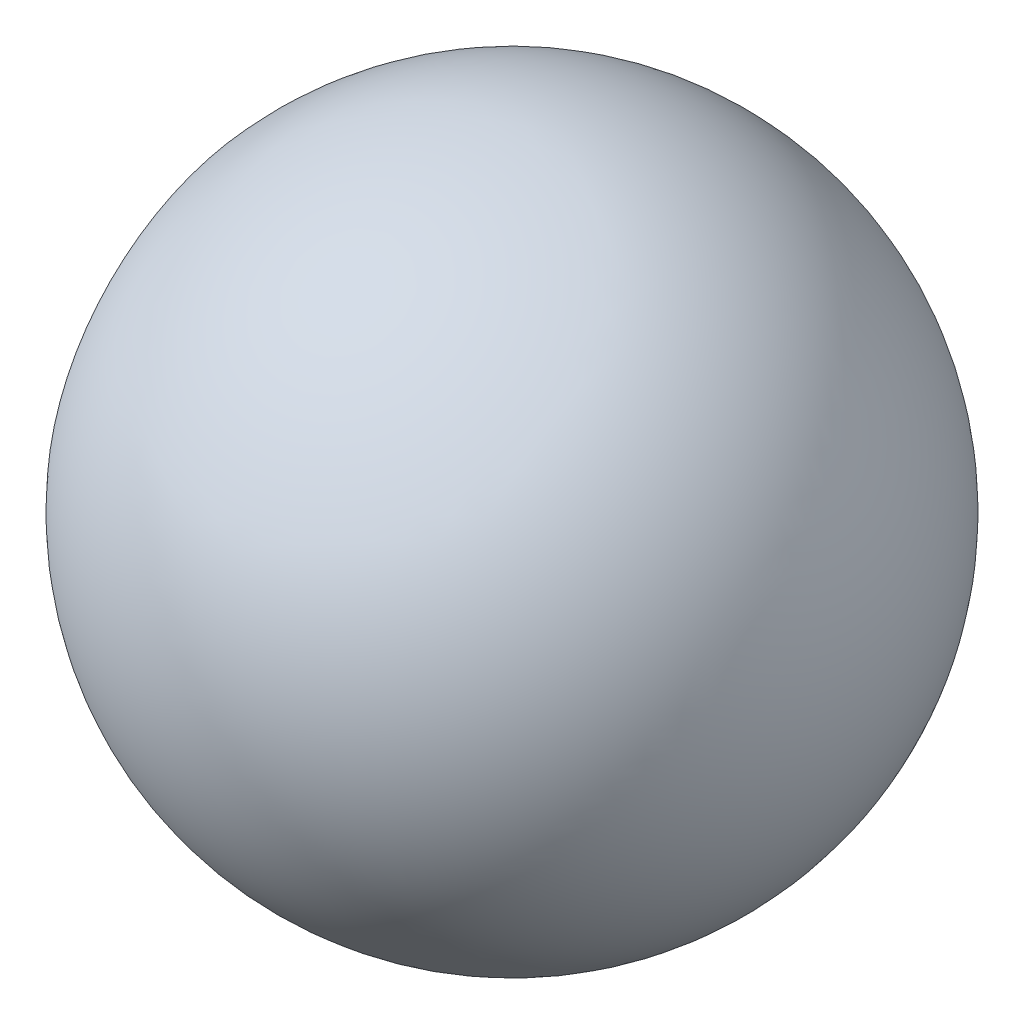
SolidWorks part; units mm, degrees
ref_plane "Front Plane" through (0, 0, 0) normal (0, 0, 1) x (1, 0, 0)
ref_plane "Top Plane" through (0, 0, 0) normal (0, 1, 0) x (1, 0, 0)
ref_plane "Right Plane" through (0, 0, 0) normal (1, 0, 0) x (0, 0, -1)
sketch "Sketch1" plane through (0, 0, 0) normal (0, 0, 1) x (1, 0, 0)
  line L0 (8, 0) -> (-6, 0)
  line L1 (-6, 5.2915) -> (-6, 0)
  arc A0 (8, 0) -> (-6, 5.2915) centre (0, 0) ccw
  dimension "D1" = 8
  dimension "D2" = 6
revolve "Revolve1" add sketch "Sketch1" angle 360 about L0
hole_wizard "M6 Tapped Hole1" positions "Sketch2" profile "Sketch3" tap size "M6" standard "ISO"
sketch "Sketch2" plane through (-6, 0, 0) normal (-1, 0, 0) x (0, 0, 1)
  point P0 (0, 0)
sketch "Sketch3" plane through (-6, 0, 0) normal (0, 1, 0) x (0, 0, 1)
  line L0 (0, 0) -> (0, 11.5022)
  line L1 (0, 11.5022) -> (2.5, 10)
  line L2 (2.5, 10) -> (2.5, 0)
  line L5 (2.5, 0) -> (0, 0)
  line L10 (0, 11.5022) -> (-2.5, 10) construction
  line L11 (0, -6.35) -> (0, 107.95) construction
  dimension "Tap Drill Dia." = 5
  dimension "Tap Drill Depth" = 10
  dimension "Drill Angle" = 118
cosmetic thread "Hole Thread1"
